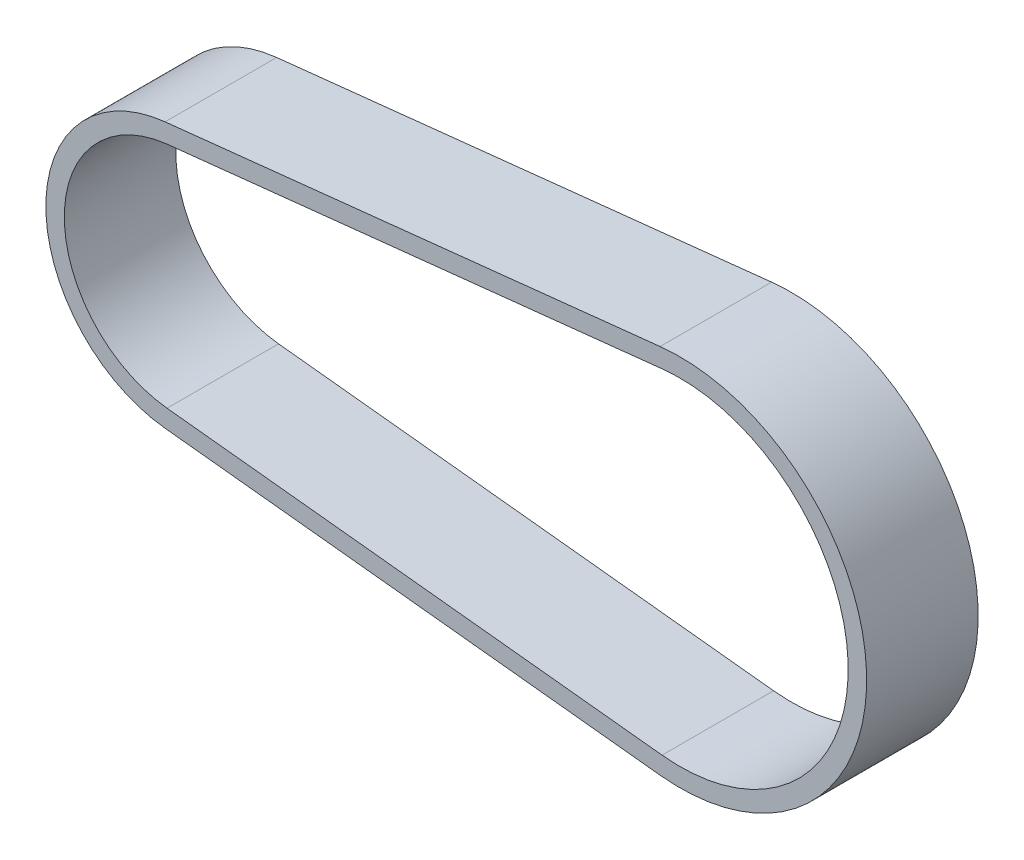
SolidWorks part; units mm, degrees
material "ﾎﾟﾘｳﾚﾀﾝ(POLYURETHANE) (11671)"
ref_plane "正面" through (0, 0, 0) normal (0, 0, 1) x (1, 0, 0)
ref_plane "平面" through (0, 0, 0) normal (0, 1, 0) x (1, 0, 0)
ref_plane "右側面" through (0, 0, 0) normal (1, 0, 0) x (0, 0, -1)
sketch "ｽｹｯﾁ1" plane through (0, 0, 0) normal (0, 0, 1) x (1, 0, 0)
  line L0 (-92.1694, 22.1537) -> (-3.385, 31.6495)
  line L1 (-89.8, 0) -> (0, 0) construction
  line L2 (-3.385, -31.6495) -> (-92.1694, -22.1537)
  arc A0 (-3.385, 31.6495) -> (-3.385, -31.6495) centre (0, 0) cw
  arc A1 (-92.1694, 22.1537) -> (-92.1694, -22.1537) centre (-89.8, 0) ccw
  dimension "D1" = 22.28
  dimension "D2" = 31.83
  dimension "D3" = 89.8
extrude "押し出し-薄板1" add sketch "ｽｹｯﾁ1" along normal blind 20 thin thin type mid plane wall 3.31
